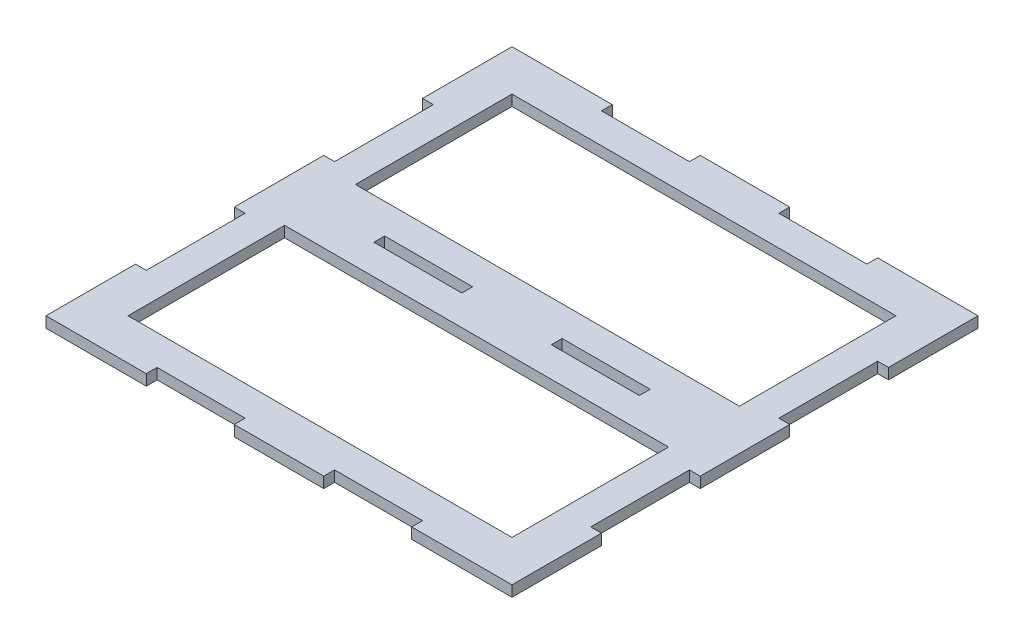
SolidWorks part; units mm, degrees
material "Бальса"
ref_plane "Спереди" through (0, 0, 0) normal (0, 0, 1) x (1, 0, 0)
ref_plane "Сверху" through (0, 0, 0) normal (0, 1, 0) x (1, 0, 0)
ref_plane "Справа" through (0, 0, 0) normal (1, 0, 0) x (0, 0, -1)
sketch "Эскиз1" plane through (0, 0, 0) normal (0, 1, 0) x (1, 0, 0)
  line L0 (0, 125) -> (250, 125) construction
  line L1 (0, 0) -> (250, 0)
  line L2 (0, 0) -> (0, 250)
  line L3 (0, 250) -> (250, 250)
  line L4 (250, 0) -> (250, 250)
  line L5 (22, 228) -> (228, 228)
  line L6 (22, 228) -> (22, 144)
  line L7 (22, 144) -> (228, 144)
  line L8 (228, 228) -> (228, 144)
  line L9 (22, 106) -> (228, 106)
  line L10 (22, 106) -> (22, 22)
  line L11 (22, 22) -> (228, 22)
  line L12 (228, 106) -> (228, 22)
  dimension "D1" = 250
  dimension "D2" = 250
  dimension "D3" = 22
  dimension "D4" = 22
  dimension "D5" = 22
  dimension "D6" = 22
  dimension "D7" = 19
  dimension "D8" = 38
extrude "Бобышка-Вытянуть1" add sketch "Эскиз1" along normal blind 5.8
sketch "Эскиз2" plane through (0, 5.8, 0) normal (0, 1, 0) x (1, 0, 0)
  line L1 (53.8, 5.8) -> (101, 5.8)
  line L2 (53.8, 5.8) -> (53.8, 0)
  line L3 (53.8, 0) -> (101, 0)
  line L4 (101, 5.8) -> (101, 0)
  line L7 (101, 122.1) -> (53.8, 122.1)
  line L8 (101, 122.1) -> (101, 127.9)
  line L9 (101, 127.9) -> (53.8, 127.9)
  line L10 (53.8, 122.1) -> (53.8, 127.9)
  line L11 (53.8, 244.2) -> (101, 244.2)
  line L12 (53.8, 244.2) -> (53.8, 250)
  line L13 (53.8, 250) -> (101, 250)
  line L14 (101, 244.2) -> (101, 250)
  line L16 (5.8, 149) -> (0, 149)
  line L17 (5.8, 149) -> (5.8, 202)
  line L18 (5.8, 202) -> (0, 202)
  line L19 (0, 149) -> (0, 202)
  line L22 (5.8, 101) -> (0, 101)
  line L23 (5.8, 101) -> (5.8, 48)
  line L24 (5.8, 48) -> (0, 48)
  line L25 (0, 101) -> (0, 48)
  line L27 (196.2, 5.8) -> (149, 5.8)
  line L28 (196.2, 5.8) -> (196.2, 0)
  line L29 (196.2, 0) -> (149, 0)
  line L30 (149, 5.8) -> (149, 0)
  line L32 (149, 122.1) -> (196.2, 122.1)
  line L33 (149, 122.1) -> (149, 127.9)
  line L34 (149, 127.9) -> (196.2, 127.9)
  line L35 (196.2, 122.1) -> (196.2, 127.9)
  line L36 (149, 244.2) -> (196.2, 244.2)
  line L37 (149, 244.2) -> (149, 250)
  line L38 (149, 250) -> (196.2, 250)
  line L39 (196.2, 244.2) -> (196.2, 250)
  line L40 (244.2, 149) -> (250, 149)
  line L41 (244.2, 149) -> (244.2, 202)
  line L42 (244.2, 202) -> (250, 202)
  line L43 (250, 149) -> (250, 202)
  line L45 (250, 250) -> (0, 250) construction
  line L46 (244.2, 48) -> (250, 48)
  line L47 (244.2, 48) -> (244.2, 101)
  line L48 (244.2, 101) -> (250, 101)
  line L49 (250, 48) -> (250, 101)
  line L50 (0, 0) -> (250, 0) construction
  line L52 (0, 250) -> (0, 0) construction
  line L53 (250, 0) -> (250, 250) construction
  line L54 (53.8, 125) -> (0, 125) construction
  line L55 (101, 125) -> (149, 125) construction
  line L56 (196.2, 125) -> (250, 125) construction
  line L57 (101, 122.1) -> (149, 122.1) construction
  point P43 (53.8, 0)
  point P44 (149, 0)
  dimension "D1" = 48
  dimension "D2" = 48
  dimension "D3" = 48
  dimension "D4" = 48
  dimension "D5" = 48
  dimension "D6" = 48
  dimension "D7" = 5.8
  dimension "D8" = 5.8
  dimension "D9" = 48
  dimension "D10" = 48
  dimension "D11" = 48
  dimension "D12" = 5.8
  dimension "D13" = 48
  dimension "D14" = 48
  dimension "D15" = 48
  dimension "D16" = 5.8
  dimension "D17" = 48
  dimension "D18" = 48
  dimension "D19" = 48
  dimension "D20" = 5.8
extrude "Вырез-Вытянуть1" cut sketch "Эскиз2" against normal up to next
